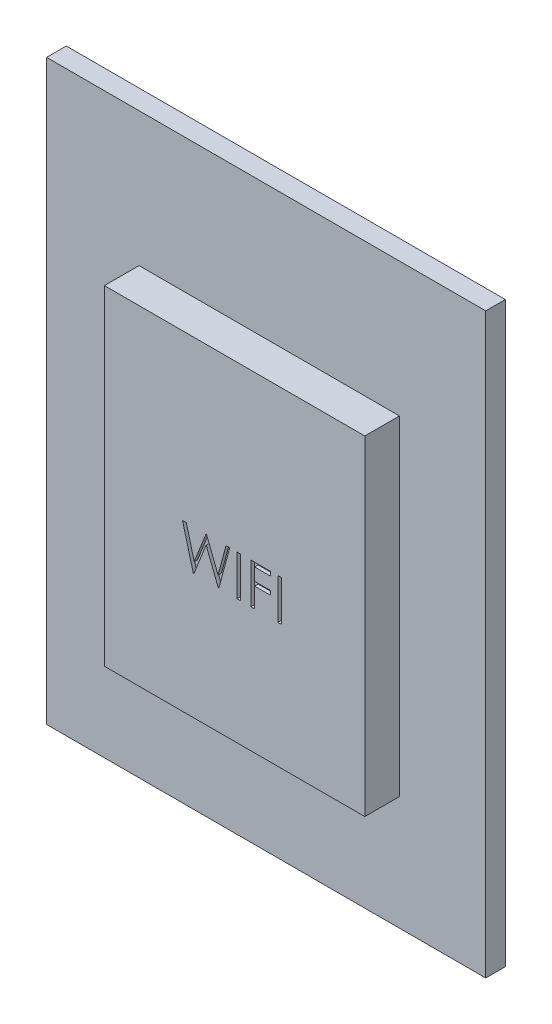
SolidWorks part; units mm, degrees
ref_plane "Front Plane" through (0, 0, 0) normal (0, 0, 1) x (1, 0, 0)
ref_plane "Top Plane" through (0, 0, 0) normal (0, 1, 0) x (1, 0, 0)
ref_plane "Right Plane" through (0, 0, 0) normal (1, 0, 0) x (0, 0, -1)
sketch "Sketch1" plane through (0, 0, 0) normal (0, 0, 1) x (1, 0, 0)
  line L1 (-19, 25) -> (19, 25)
  line L2 (-19, 25) -> (-19, -25)
  line L3 (-19, -25) -> (19, -25)
  line L4 (19, 25) -> (19, -25)
  point P4 (0, 25)
  point P5 (-19, 0)
  dimension "D1" = 38
  dimension "D2" = 50
extrude "Boss-Extrude1" add sketch "Sketch1" along normal blind 1.7
sketch "Sketch2" plane through (0, 0, 1.7) normal (0, 0, 1) x (1, 0, 0)
  line L0 (-19, 25) -> (-19, -25) construction
  line L1 (19, 25) -> (-19, 25) construction
  circle A0 centre (-13, 19) radius 2.05
  circle A1 centre (47, 19) radius 2.05
  circle A2 centre (47, -51) radius 2.05
  circle A3 centre (-13, -51) radius 2.05
  dimension "D3" = 4.1
  dimension "D1" = 6
  dimension "D2" = 6
  dimension "D4" = 2
  dimension "D5" = 2
extrude "Cut-Extrude1" [suppressed] cut sketch "Sketch2" against normal through all
sketch "Sketch3" plane through (0, 0, 1.7) normal (0, 0, 1) x (1, 0, 0)
  line L1 (-11.0004, 13.3917) -> (11.534, 13.3917)
  line L2 (-11.0004, 13.3917) -> (-11.0004, -15.1342)
  line L3 (-11.0004, -15.1342) -> (11.534, -15.1342)
  line L4 (11.534, 13.3917) -> (11.534, -15.1342)
extrude "Boss-Extrude2" add sketch "Sketch3" along normal blind 3
sketch "Sketch4" plane through (0, 0, 4.7) normal (0, 0, 1) x (1, 0, 0)
  text T0 "WIFI"
extrude "Cut-Extrude2" cut sketch "Sketch4" against normal blind 0.3
